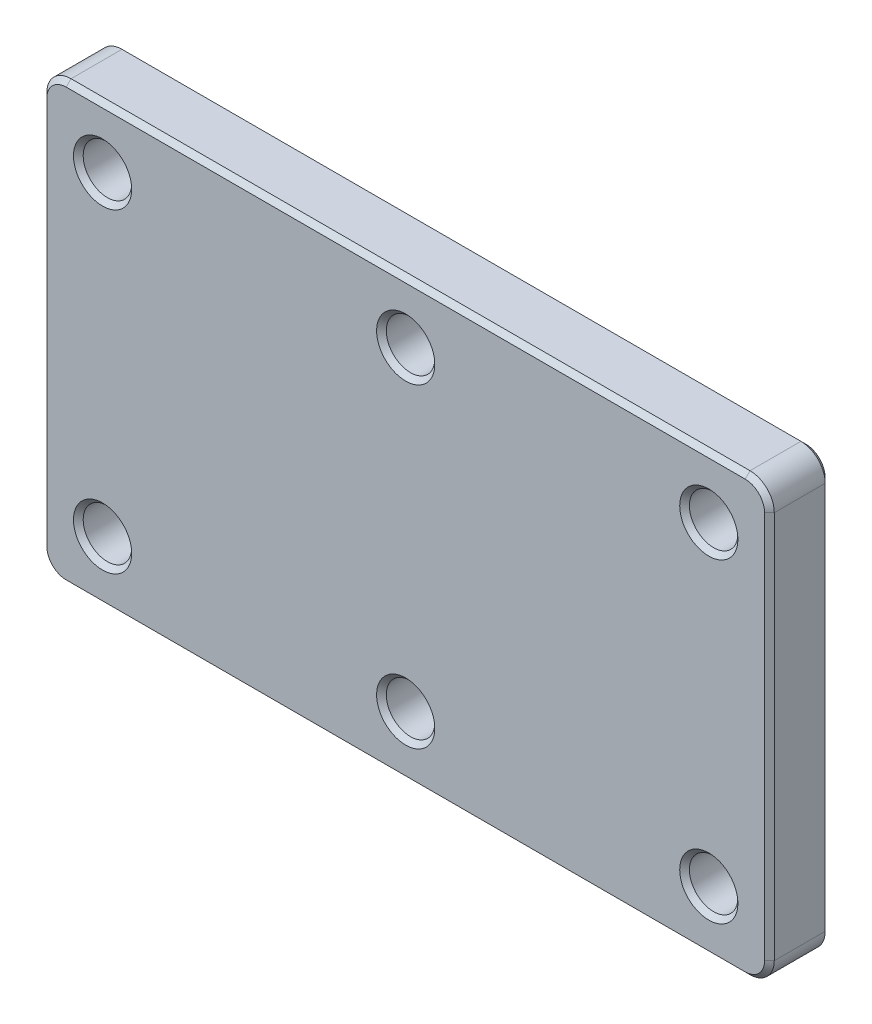
SolidWorks part; units mm, degrees
ref_plane "前基準面" through (0, 0, 0) normal (0, 0, 1) x (1, 0, 0)
ref_plane "上基準面" through (0, 0, 0) normal (0, 1, 0) x (1, 0, 0)
ref_plane "右基準面" through (0, 0, 0) normal (1, 0, 0) x (0, 0, -1)
sketch "草圖1" plane through (0, 0, 0) normal (0, 0, 1) x (1, 0, 0)
  line L1 (0, 0) -> (300, 0)
  line L2 (0, 0) -> (0, 180)
  line L3 (0, 180) -> (300, 180)
  line L4 (300, 0) -> (300, 180)
  dimension "D1" = 300
  dimension "D2" = 180
extrude "填料-伸長1" add sketch "草圖1" along normal blind 25
fillet "圓角1" radius 10 4 edges at (300, 0, 12.5) (0, 0, 12.5) (300, 180, 12.5) (0, 180, 12.5)
sketch "草圖2" plane through (0, 0, 25) normal (0, 0, 1) x (1, 0, 0)
  line L0 (150, 155) -> (150, 25)
  line L1 (25, 155) -> (275, 155)
  line L2 (25, 155) -> (25, 25)
  line L3 (25, 25) -> (275, 25)
  line L4 (275, 155) -> (275, 25)
  line L5 (150, 25) -> (150, 0)
  line L6 (10, 0) -> (290, 0) construction
  dimension "D1" = 250
  dimension "D2" = 130
  dimension "D3" = 25
hole_wizard "Ø20.0mm 定位孔1" positions "草圖3" profile "草圖4" hole size "Ø20.0" standard "ISO" end condition through all
sketch "草圖3" plane through (0, 0, 25) normal (0, 0, 1) x (1, 0, 0)
  point P0 (25, 155)
  point P3 (25, 25)
  point P6 (150, 25)
  point P9 (150, 155)
  point P12 (275, 155)
  point P15 (275, 25)
sketch "草圖4" plane through (25, 155, 25) normal (1, 0, 0) x (0, -1, 0)
  line L0 (0, 0) -> (0, 25)
  line L1 (0, 25) -> (10, 25)
  line L2 (10, 25) -> (10, 0)
  line L5 (10, 0) -> (0, 0)
  line L11 (0, -6.35) -> (0, 107.95) construction
  dimension "貫穿孔直徑" = 20
  dimension "貫穿孔深度" = 25
chamfer "導角1" distance 2 angle 45 28 edges at (35, 25, 25) (2.9289, 2.9289, 25) (0, 90, 25) (2.9289, 177.0711, 25) (150, 180, 25) (297.0711, 177.0711, 25) (300, 90, 25) (297.0711, 2.9289, 25) (150, 0, 25) (285, 25, 25) (285, 155, 25) (160, 155, 25) (160, 25, 25) (35, 155, 25) (297.0711, 177.0711, 0) (150, 180, 0) (2.9289, 177.0711, 0) (0, 90, 0) (2.9289, 2.9289, 0) (150, 0, 0) (297.0711, 2.9289, 0) (300, 90, 0) (285, 25, 0) (285, 155, 0) (160, 155, 0) (160, 25, 0) (35, 25, 0) (35, 155, 0)
